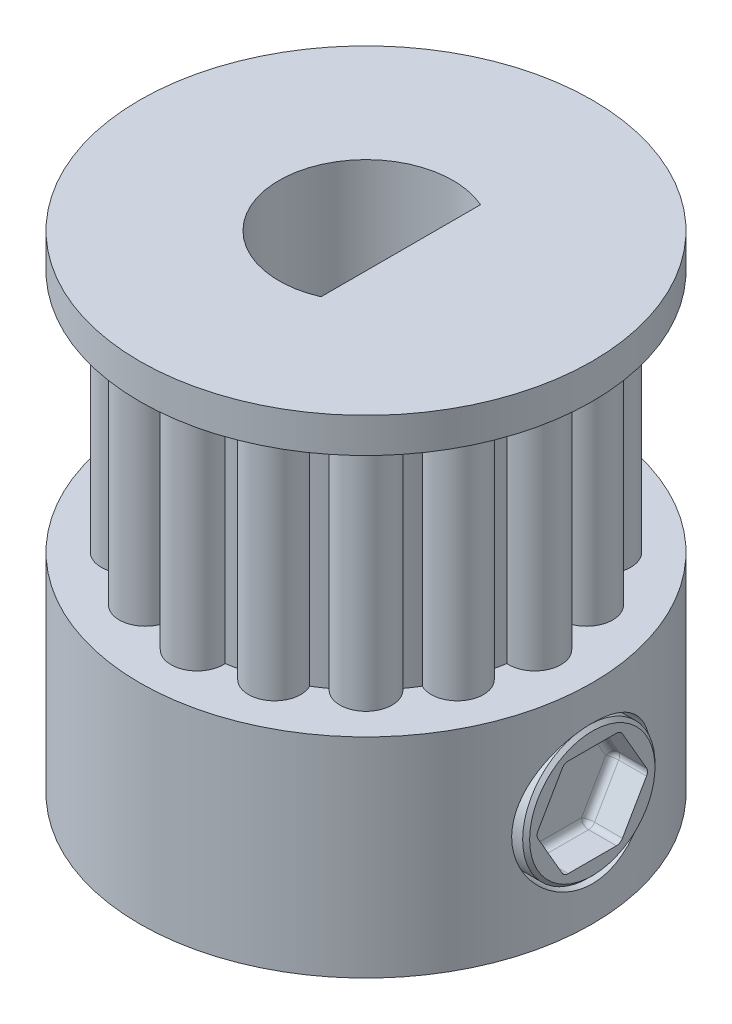
SolidWorks part; units mm, degrees
material "1060 Alloy"
ref_plane "Front Plane" through (0, 0, 0) normal (0, 0, 1) x (1, 0, 0)
ref_plane "Top Plane" through (0, 0, 0) normal (0, 1, 0) x (1, 0, 0)
ref_plane "Right Plane" through (0, 0, 0) normal (1, 0, 0) x (0, 0, -1)
sketch "Sketch1" plane through (0, 0, 0) normal (0, 0, 1) x (1, 0, 0)
  line L0 (2.5, 0) -> (2.5, 14)
  line L1 (2.5, 14) -> (6.5, 14)
  line L2 (6.5, 14) -> (6.5, 13)
  line L3 (6.5, 13) -> (4.85, 13)
  line L4 (4.85, 13) -> (4.85, 6)
  line L5 (4.85, 6) -> (6.5, 6)
  line L6 (6.5, 6) -> (6.5, 0)
  line L7 (6.5, 0) -> (2.5, 0)
  line L8 (0, 0) -> (0, 14) construction
  dimension "D1" = 14
  dimension "D2" = 9.7
  dimension "D3" = 6
  dimension "D4" = 7
  dimension "D5" = 13
  dimension "D6" = 5
revolve "Revolve1" add sketch "Sketch1" angle 360 about L8
sketch "Sketch2" plane through (0, 6, 0) normal (0, 1, 0) x (1, 0, 0)
  circle A0 centre (0, 0) radius 4.85 construction
  circle A1 centre (0, 0) radius 4.85
  arc A2 (0.7478, 4.792) -> (-0.7478, 4.792) centre (0, 4.85) ccw
  arc A3 (2.5247, 4.1411) -> (1.143, 4.7134) centre (1.856, 4.4808) ccw
  arc A4 (3.9172, 2.8597) -> (2.8597, 3.9172) centre (3.4295, 3.4295) ccw
  arc A5 (4.7134, 1.143) -> (4.1411, 2.5247) centre (4.4808, 1.856) ccw
  arc A6 (4.792, -0.7478) -> (4.792, 0.7478) centre (4.85, 0) ccw
  arc A7 (4.1411, -2.5247) -> (4.7134, -1.143) centre (4.4808, -1.856) ccw
  arc A8 (2.8597, -3.9172) -> (3.9172, -2.8597) centre (3.4295, -3.4295) ccw
  arc A9 (1.143, -4.7134) -> (2.5247, -4.1411) centre (1.856, -4.4808) ccw
  arc A10 (-0.7478, -4.792) -> (0.7478, -4.792) centre (0, -4.85) ccw
  arc A11 (-2.5247, -4.1411) -> (-1.143, -4.7134) centre (-1.856, -4.4808) ccw
  arc A12 (-3.9172, -2.8597) -> (-2.8597, -3.9172) centre (-3.4295, -3.4295) ccw
  arc A13 (-4.7134, -1.143) -> (-4.1411, -2.5247) centre (-4.4808, -1.856) ccw
  arc A14 (-4.792, 0.7478) -> (-4.792, -0.7478) centre (-4.85, 0) ccw
  arc A15 (-4.1411, 2.5247) -> (-4.7134, 1.143) centre (-4.4808, 1.856) ccw
  arc A16 (-2.8597, 3.9172) -> (-3.9172, 2.8597) centre (-3.4295, 3.4295) ccw
  arc A17 (-1.143, 4.7134) -> (-2.5247, 4.1411) centre (-1.856, 4.4808) ccw
  point P66 (0, 0)
  circle M3 centre (0, 0) radius 4.85
  dimension "D1" = 0.75
  dimension "D2" = 16
extrude "Boss-Extrude1" add sketch "Sketch2" along normal up to surface (7 mm away) contours A16 M3 | A17 M3 | A2 M3 | A3 M3 | A4 M3 | A5 M3 | A6 M3 | A7 M3 | A8 M3 | A9 M3 | A10 M3 | A11 M3 | A12 M3 | A13 M3 | A14 M3 | A15 M3 | A1
sketch "Sketch3" plane through (0, 0, 0) normal (0, 1, 0) x (1, 0, 0)
  line L0 (1, 2.2913) -> (1, -2.2913)
  circle A0 centre (0, 0) radius 2.5 construction
  arc A1 (1, -2.2913) -> (1, 2.2913) centre (0, 0) ccw
  dimension "D1" = 1
extrude "Boss-Extrude2" add sketch "Sketch3" along normal up to surface (14 mm away) up to face at (0, 14, -2.5)
sketch "Sketch4" plane through (1, 0, 0) normal (-1, 0, 0) x (0, 0, 1)
  line L0 (0, 0) -> (0, 6) construction
  line L1 (-2.2913, 6) -> (2.2913, 6) construction
  line L4 (6.5, 6) -> (-6.5, 6) construction
  line L6 (2.2913, 14) -> (2.2913, 0) construction
  circle A0 centre (0, 3) radius 2
  point P6 (0, 6)
  point P14 (0, 3)
  dimension "D1" = 4
extrude "Cut-Extrude1" cut sketch "Sketch4" against normal through all
sketch "Sketch5" plane through (1, 0, 0) normal (-1, 0, 0) x (0, 0, 1)
  circle A0 centre (0, 3) radius 1.9
  circle A1 centre (0, 3) radius 2 construction
  dimension "D1" = 0.1
extrude "Boss-Extrude3" add sketch "Sketch5" against normal blind 5.5 separate body
sketch "Sketch6" plane through (6.5, 0, 0) normal (1, 0, 0) x (0, 0, -1)
  line L1 (1.6166, 3) -> (0.8083, 4.4)
  line L2 (0.8083, 4.4) -> (-0.8083, 4.4)
  line L3 (-0.8083, 4.4) -> (-1.6166, 3)
  line L4 (-1.6166, 3) -> (-0.8083, 1.6)
  line L5 (-0.8083, 1.6) -> (0.8083, 1.6)
  line L6 (0.8083, 1.6) -> (1.6166, 3)
  circle A0 centre (0, 3) radius 1.4 construction
  circle A1 centre (0, 3) radius 1.9 construction
  dimension "D1" = 0.5
extrude "Cut-Extrude2" cut sketch "Sketch6" against normal blind 1
fillet "Fillet1" radius 0.2 12 edges at (6, 1.6, -0.8083) (6, 3, -1.6166) (6, 4.4, -0.8083) (6, 4.4, 0.8083) (6, 3, 1.6166) (6, 1.6, 0.8083) (5.5, 1.6, 0) (5.5, 2.3, 1.2124) (5.5, 3.7, 1.2124) (5.5, 4.4, 0) (5.5, 3.7, -1.2124) (5.5, 2.3, -1.2124)
chamfer "Chamfer1" distance 0.1 angle 45 1 edges at (6.5, 3, 1.9)
